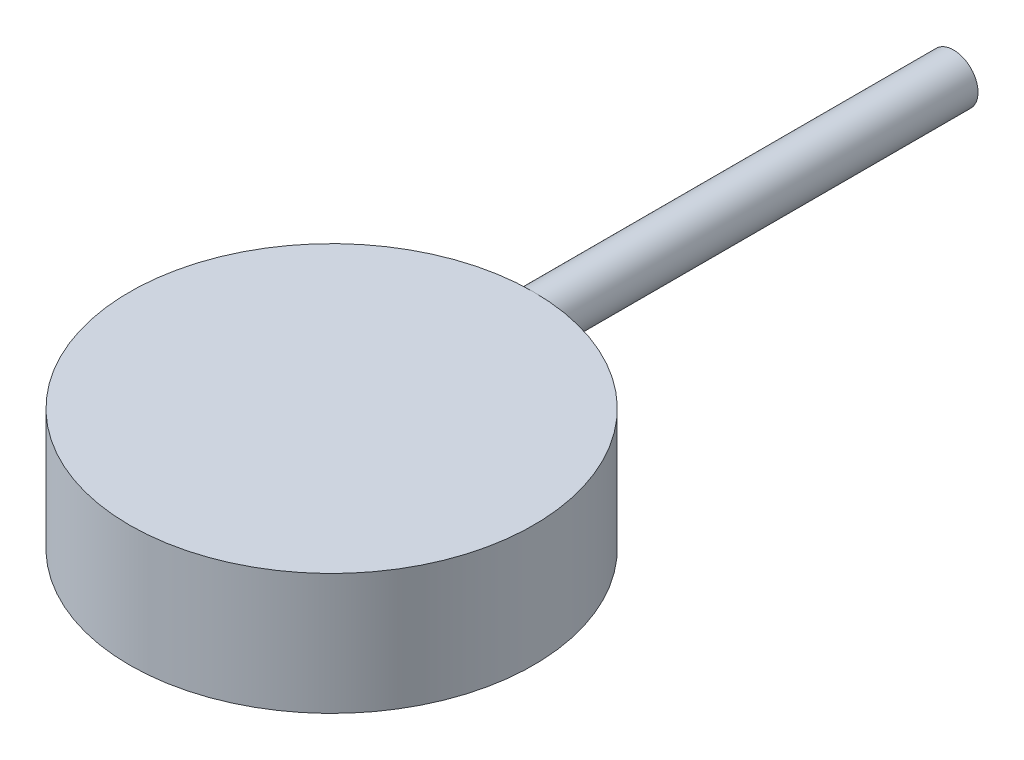
SolidWorks part; units mm, degrees
ref_plane "Front Plane" through (0, 0, 0) normal (0, 0, 1) x (1, 0, 0)
ref_plane "Top Plane" through (0, 0, 0) normal (0, 1, 0) x (1, 0, 0)
ref_plane "Right Plane" through (0, 0, 0) normal (1, 0, 0) x (0, 0, -1)
sketch "Sketch1" plane through (0, 0, 0) normal (0, 1, 0) x (1, 0, 0)
  circle A0 centre (0, 0) radius 41.25
  dimension "D1" = 82.5
extrude "Boss-Extrude1" add sketch "Sketch1" along normal blind 5.08 and the other way blind 19.67
sketch "Sketch2" plane through (0, 0, 0) normal (0, 1, 0) x (1, 0, 0)
  line L0 (0, 127) -> (0, 0)
  line L1 (-5, 127) -> (0, 127)
  line L2 (-5, 127) -> (-5, 0)
  line L3 (-5, 0) -> (0, 0)
  dimension "D2" = 127
revolve "Revolve1" add sketch "Sketch2" angle 360 about L0
